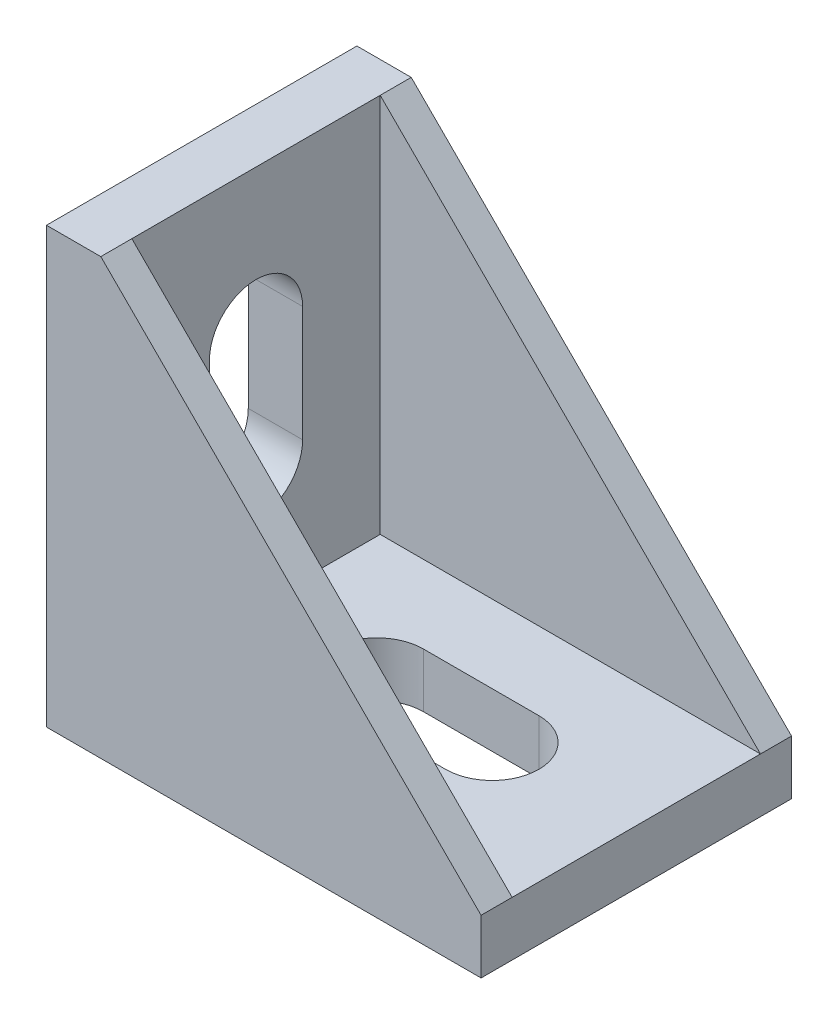
SolidWorks part; units mm, degrees
ref_plane "Front Plane" through (0, 0, 0) normal (0, 0, 1) x (1, 0, 0)
ref_plane "Top Plane" through (0, 0, 0) normal (0, 1, 0) x (1, 0, 0)
ref_plane "Right Plane" through (0, 0, 0) normal (1, 0, 0) x (0, 0, -1)
sketch "Sketch1" plane through (0, 0, 0) normal (1, 0, 0) x (0, 0, -1)
  line L1 (0, 0) -> (20, 0)
  line L2 (0, 0) -> (0, 28)
  line L3 (0, 28) -> (20, 28)
  line L4 (20, 0) -> (20, 28)
  dimension "D1" = 20
  dimension "D2" = 28
extrude "Boss-Extrude1" add sketch "Sketch1" along normal blind 3.5
sketch "Sketch2" plane through (3.5, 0, 0) normal (1, 0, 0) x (0, 0, -1)
  line L0 (20, 0) -> (20, 28) construction
  line L1 (0, 0) -> (20, 0)
  line L2 (0, 0) -> (0, 3.5)
  line L3 (0, 3.5) -> (20, 3.5)
  line L4 (20, 0) -> (20, 3.5)
  dimension "D1" = 3.5
extrude "Boss-Extrude2" add sketch "Sketch2" along normal blind 24.5
sketch "Sketch3" plane through (0, 0, -20) normal (0, 0, -1) x (-1, 0, 0)
  line L1 (-28, 0) -> (-28, 3.5)
  line L4 (-28, 3.5) -> (-3.5, 28)
  line L6 (0, 0) -> (-28, 0)
  line L7 (-3.5, 28) -> (0, 28)
  line L8 (0, 28) -> (0, 0)
extrude "Boss-Extrude3" add sketch "Sketch3" against normal blind 2
sketch "Sketch4" plane through (0, 0, 0) normal (0, 0, 1) x (1, 0, 0)
  line L11 (3.5, 28) -> (0, 28)
  line L12 (28, 3.5) -> (3.5, 28)
  line L13 (28, 0) -> (28, 3.5)
  line L14 (0, 0) -> (28, 0)
  line L15 (0, 28) -> (0, 0)
  line L16 (3.5, 28) -> (0, 28)
  line L17 (28, 3.5) -> (3.5, 28)
  line L24 (28, 0) -> (28, 3.5)
  line L25 (0, 0) -> (28, 0)
  line L26 (0, 28) -> (0, 0)
  dimension "D1" = 0
extrude "Boss-Extrude4" add sketch "Sketch4" against normal blind 2
sketch "Sketch5" plane through (0, 3.5, 0) normal (0, 1, 0) x (1, 0, 0)
  line L0 (18.7188, 10) -> (11.2812, 10) construction
  line L1 (18.7188, 7) -> (11.2812, 7)
  line L2 (18.7188, 13) -> (11.2812, 13)
  arc A0 (18.7188, 7) -> (18.7188, 13) centre (18.7188, 10) ccw
  arc A1 (11.2812, 13) -> (11.2812, 7) centre (11.2812, 10) ccw
  point P2 (15, 10)
  dimension "D4" = 3
  dimension "D1" = 10
  dimension "D2" = 15
  dimension "D3" = 7.4376
extrude "Cut-Extrude1" cut sketch "Sketch5" against normal through all
sketch "Sketch6" plane through (3.5, 0, 0) normal (1, 0, 0) x (0, 0, -1)
  line L0 (10, 11.28) -> (10, 18.72) construction
  line L1 (7, 11.28) -> (7, 18.72)
  line L2 (13, 11.28) -> (13, 18.72)
  arc A0 (7, 11.28) -> (13, 11.28) centre (10, 11.28) ccw
  arc A1 (13, 18.72) -> (7, 18.72) centre (10, 18.72) ccw
  point P2 (10, 15)
  point P7 (0, 0)
  point P10 (2.7324, 9.5375)
  dimension "D3" = 3
  dimension "D1" = 15
  dimension "D2" = 10
  dimension "D4" = 7.44
extrude "Cut-Extrude2" cut sketch "Sketch6" against normal through all
